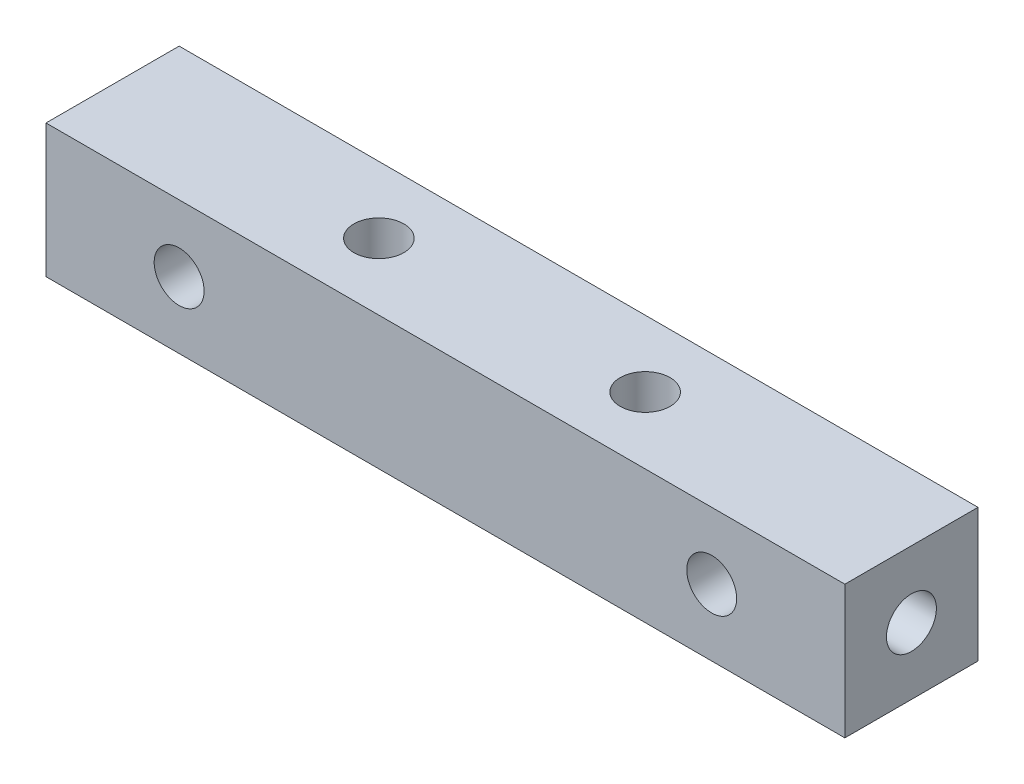
SolidWorks part; units mm, degrees
ref_plane "前视基准面" through (0, 0, 0) normal (0, 0, 1) x (1, 0, 0)
ref_plane "上视基准面" through (0, 0, 0) normal (0, 1, 0) x (1, 0, 0)
ref_plane "右视基准面" through (0, 0, 0) normal (1, 0, 0) x (0, 0, -1)
other "Configuration Table"
sketch "草图1" plane through (0, 0, 0) normal (0, 1, 0) x (1, 0, 0)
  line L1 (-24, 4) -> (24, 4)
  line L2 (-24, 4) -> (-24, -4)
  line L3 (-24, -4) -> (24, -4)
  line L4 (24, 4) -> (24, -4)
  line L5 (-24, 4) -> (24, -4) construction
  line L6 (-24, -4) -> (24, 4) construction
  point P0 (0, 0)
  dimension "D1" = 8
  dimension "D2" = 48
extrude "凸台-拉伸1" add sketch "草图1" along normal blind 8
sketch "草图2" plane through (0, 0, 4) normal (0, 0, 1) x (1, 0, 0)
  line L0 (-16, 4) -> (16, 4) construction
  line L1 (0, 4) -> (0, 0) construction
  circle A0 centre (-16, 4) radius 1.5
  circle A1 centre (16, 4) radius 1.5
  dimension "D2" = 3
  dimension "D1" = 4
  dimension "D3" = 32
extrude "切除-拉伸1" cut sketch "草图2" against normal blind 10
sketch "草图3" plane through (0, 8, 0) normal (0, 1, 0) x (1, 0, 0)
  line L0 (-8, 0) -> (8, 0) construction
  circle A0 centre (-8, 0) radius 1.5
  circle A1 centre (8, 0) radius 1.5
  point P4 (0, 0)
  dimension "D2" = 3
  dimension "D1" = 16
extrude "切除-拉伸2" cut sketch "草图3" against normal blind 10
sketch "草图4" plane through (-24, 0, 0) normal (-1, 0, 0) x (0, 0, 1)
  line L0 (0, 4) -> (4, 4) construction
  line L1 (4, 8) -> (4, 0) construction
  line L2 (0, 4) -> (0, 0) construction
  line L3 (-4, 0) -> (4, 0) construction
  circle A0 centre (0, 4) radius 1.5
  dimension "D1" = 3
extrude "切除-拉伸3" cut sketch "草图4" against normal blind 8
mirror "镜向1" about plane through (0, 0, 0) normal (1, 0, 0) of "切除-拉伸3"
